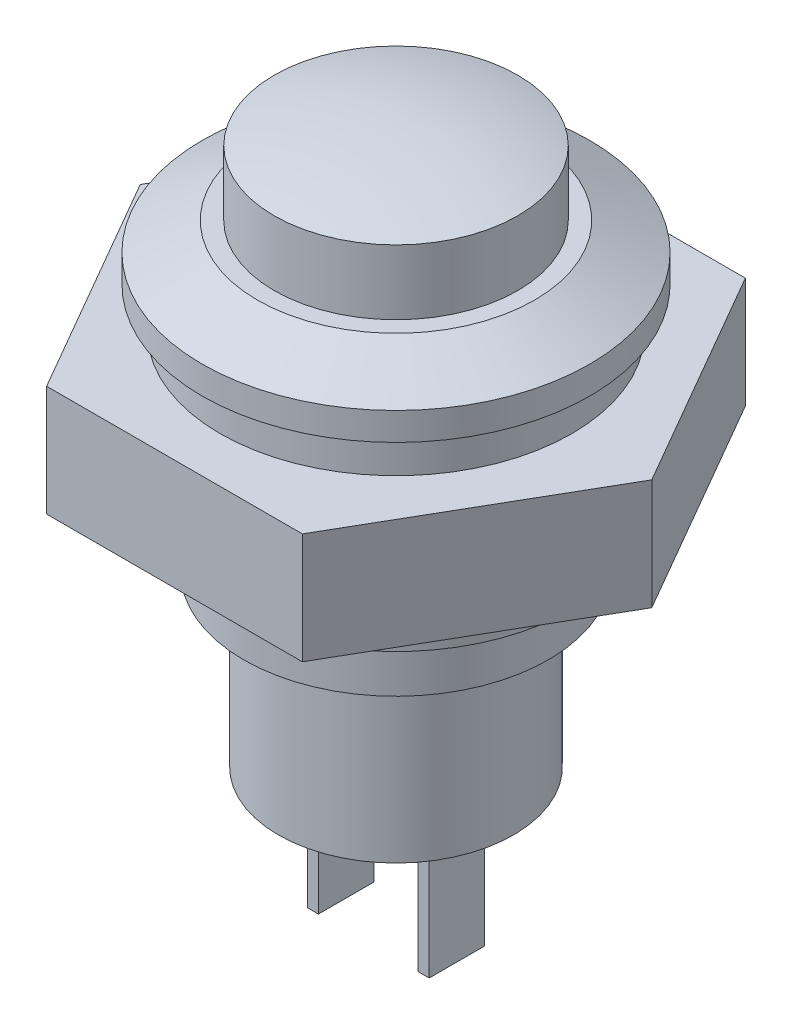
SolidWorks part; units mm, degrees
ref_plane "Plan de face" through (0, 0, 0) normal (0, 0, 1) x (1, 0, 0)
ref_plane "Plan de dessus" through (0, 0, 0) normal (0, 1, 0) x (1, 0, 0)
ref_plane "Plan de droite" through (0, 0, 0) normal (1, 0, 0) x (0, 0, -1)
sketch "Esquisse1" plane through (0, 0, 0) normal (0, 0, 1) x (1, 0, 0)
  line L0 (0, 15.5745) -> (0, -20.5934) construction
  line L2 (4.4, 4.3402) -> (4.4, 2)
  line L3 (4.4, 2) -> (7, 2)
  line L4 (7, 2) -> (7, 0)
  line L5 (7, 0) -> (6.35, 0)
  line L6 (6.35, 0) -> (6.35, -7)
  line L7 (6.35, -7) -> (5.5, -7)
  line L8 (5.5, -7) -> (5.5, -9)
  line L9 (5.5, -9) -> (4.25, -9)
  line L10 (0, -15.1) -> (0, 5)
  line L12 (4.25, -9) -> (4.25, -15.1)
  line L13 (4.25, -15.1) -> (0, -15.1)
  arc A0 (0, 5) -> (4.4, 4.3402) centre (0, -10) cw
  dimension "D1" = 8.8
  dimension "D11" = 15
  dimension "D2" = 3
  dimension "D3" = 14
  dimension "D4" = 2
  dimension "D5" = 12.7
  dimension "D6" = 17.1
  dimension "D7" = 7
  dimension "D8" = 2
  dimension "D9" = 11
  dimension "D10" = 8.5
revolve "Révolution1" add sketch "Esquisse1" angle 360 about L0
sketch "Esquisse2" plane through (0, 0, 0) normal (0, -1, 0) x (1, 0, 0)
  line L1 (4.6188, -8) -> (9.2376, 0)
  line L2 (9.2376, 0) -> (4.6188, 8)
  line L3 (4.6188, 8) -> (-4.6188, 8)
  line L4 (-4.6188, 8) -> (-9.2376, 0)
  line L5 (-9.2376, 0) -> (-4.6188, -8)
  line L6 (-4.6188, -8) -> (4.6188, -8)
  circle A0 centre (0, 0) radius 8 construction
  dimension "D1" = 16
extrude "Boss.-Extru.1" add sketch "Esquisse2" along normal blind 4 from offset 1.5
chamfer "Chanfrein1" distance 1 distance2 2 1 edges at (0, 2, 7)
sketch "Esquisse3" plane through (0, -15.1, 0) normal (0, -1, 0) x (1, 0, 0)
  line L1 (-2.2, 1) -> (-1.8, 1)
  line L2 (-2.2, 1) -> (-2.2, -1)
  line L3 (-2.2, -1) -> (-1.8, -1)
  line L4 (-1.8, 1) -> (-1.8, -1)
  line L5 (-2.2, 1) -> (-1.8, -1) construction
  line L6 (-2.2, -1) -> (-1.8, 1) construction
  point P0 (-2, 0)
  dimension "D1" = 2
  dimension "D2" = 0.4
  dimension "D3" = 2
extrude "Boss.-Extru.2" add sketch "Esquisse3" along normal blind 5
mirror "Symétrie1" about plane through (0, 0, 0) normal (1, 0, 0) of "Boss.-Extru.2"
